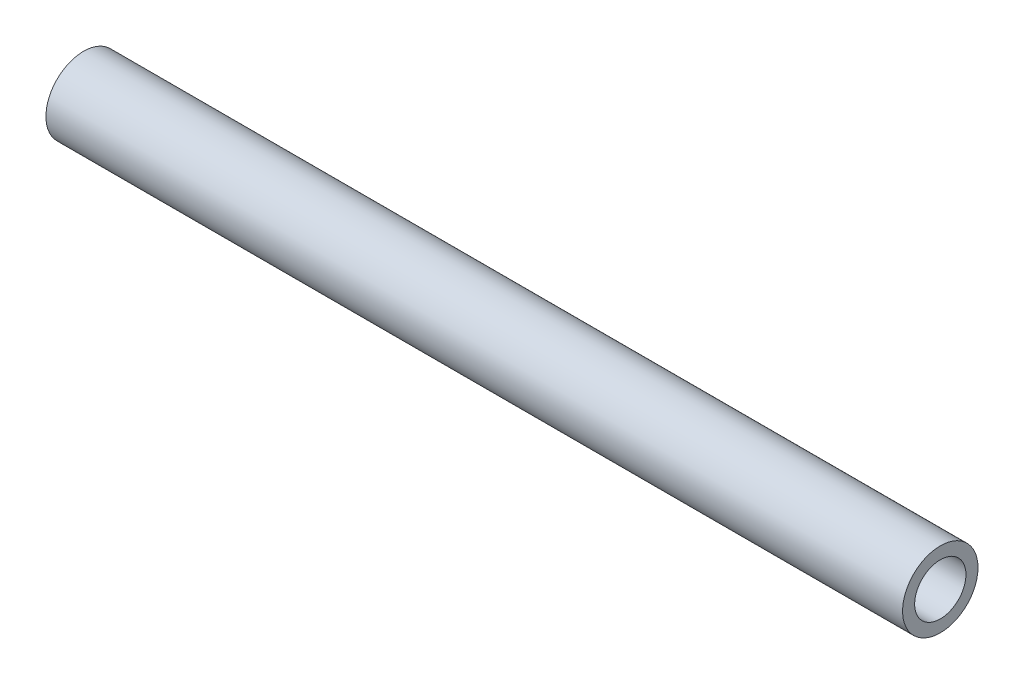
SolidWorks part; units mm, degrees
ref_plane "Front Plane" through (0, 0, 0) normal (0, 0, 1) x (1, 0, 0)
ref_plane "Top Plane" through (0, 0, 0) normal (0, 1, 0) x (1, 0, 0)
ref_plane "Right Plane" through (0, 0, 0) normal (1, 0, 0) x (0, 0, -1)
sketch "Sketch1" plane through (0, 0, 0) normal (1, 0, 0) x (0, 0, -1)
  circle A0 centre (0, 0) radius 4.25
  circle A1 centre (0, 0) radius 6.25
  dimension "D1" = 8.5
  dimension "D2" = 2
extrude "Boss-Extrude1" add sketch "Sketch1" along normal blind 142
